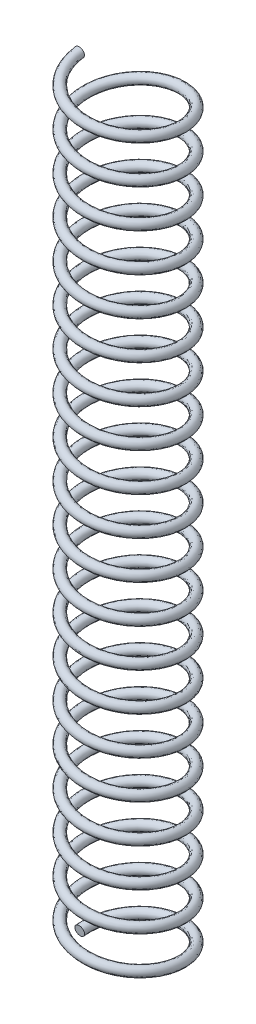
SolidWorks part; units mm, degrees
ref_plane "Front Plane" through (0, 0, 0) normal (0, 0, 1) x (1, 0, 0)
ref_plane "Top Plane" through (0, 0, 0) normal (0, 1, 0) x (1, 0, 0)
ref_plane "Right Plane" through (0, 0, 0) normal (1, 0, 0) x (0, 0, -1)
sketch "Sketch1" plane through (0, 0, 0) normal (0, 1, 0) x (1, 0, 0)
  circle A0 centre (0, 0) radius 2.54
  dimension "D1" = 5.08
curve "Helix/Spiral1" pitch 2 height 40 turns 20
sweep "Sweep1" add path "Helix/Spiral1" circular profile diameter 0.508 parameters "D3"=0.508
